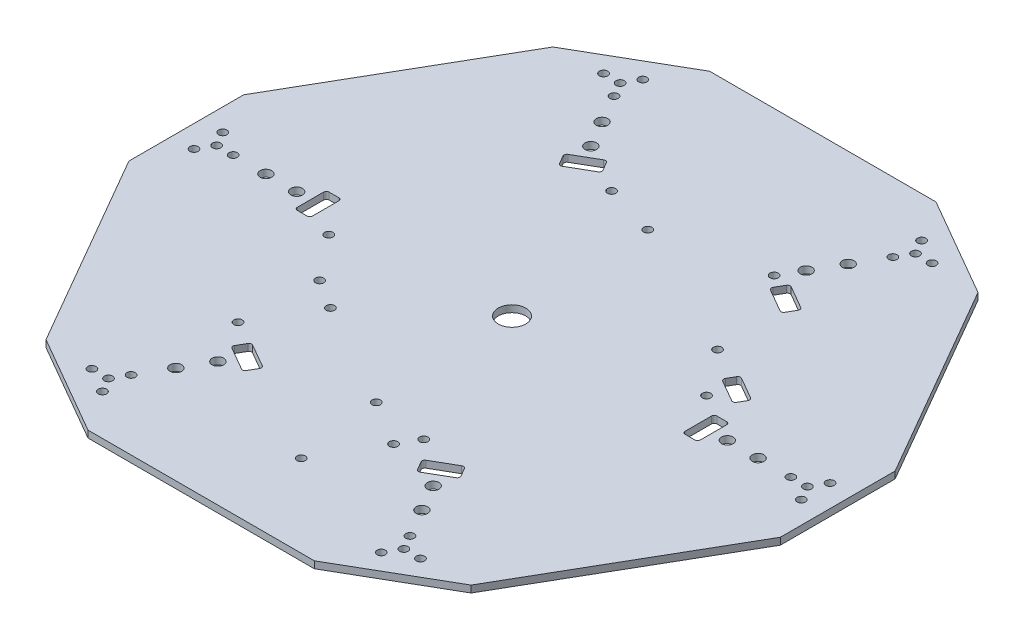
SolidWorks part; units mm, degrees
ref_plane "前视基准面" through (0, 0, 0) normal (0, 0, 1) x (1, 0, 0)
ref_plane "上视基准面" through (0, 0, 0) normal (0, 1, 0) x (1, 0, 0)
ref_plane "右视基准面" through (0, 0, 0) normal (1, 0, 0) x (0, 0, -1)
other "Configuration Table"
sketch "草图2" plane through (0, 0, 0) normal (0, 1, 0) x (1, 0, 0)
  line L1 (45, 0) -> (22.5, 38.9711)
  line L2 (22.5, 38.9711) -> (-22.5, 38.9711)
  line L3 (-22.5, 38.9711) -> (-45, 0)
  line L4 (-45, 0) -> (-22.5, -38.9711)
  line L5 (-22.5, -38.9711) -> (22.5, -38.9711)
  line L6 (22.5, -38.9711) -> (45, 0)
  line L7 (-54.5, 0) -> (-27.25, -47.1984)
  line L8 (-27.25, -47.1984) -> (27.25, -47.1984)
  line L9 (27.25, -47.1984) -> (54.5, 0)
  line L10 (54.5, 0) -> (27.25, 47.1984)
  line L11 (27.25, 47.1984) -> (-27.25, 47.1984)
  line L12 (-27.25, 47.1984) -> (-54.5, 0)
  circle A0 centre (0, 0) radius 38.9711 construction
  circle A1 centre (0, 0) radius 47.1984 construction
  circle A2 centre (0, 0) radius 5
  dimension "D3" = 10
  dimension "D1" = 45
  dimension "D2" = 9.5
extrude "凸台-拉伸1" add sketch "草图2" along normal blind 2.5 contours L5 L6 L1 L2 L3 L4 | L11 L12 L7 L8 L9 L10 L6 L5 L4 L3 L2 L1
sketch "草图3" plane through (0, 2.5, 0) normal (0, 1, 0) x (1, 0, 0)
  line L7 (-45, 0) -> (-22.5, -38.9711) construction
  line L8 (-22.5, -38.9711) -> (22.5, -38.9711) construction
  line L9 (22.5, -38.9711) -> (45, 0) construction
  line L10 (45, 0) -> (22.5, 38.9711) construction
  line L11 (22.5, 38.9711) -> (-22.5, 38.9711) construction
  line L12 (-22.5, 38.9711) -> (-45, 0) construction
  circle A0 centre (0, 0) radius 38.9711 construction
  circle A7 centre (-22.5, 38.9711) radius 2.1
  circle A8 centre (22.5, 38.9711) radius 2.1
  circle A9 centre (45, 0) radius 2.1
  circle A10 centre (22.5, -38.9711) radius 2.1
  circle A11 centre (-22.5, -38.9711) radius 2.1
  circle A12 centre (-45, 0) radius 2.1
  point P23 (0, 0)
  point P24 (0, 0)
  dimension "D2" = 4.2
  dimension "D1" = 45
  dimension "D3" = 6
extrude "切除-拉伸1" [suppressed] cut sketch "草图3" against normal blind 2.5
sketch "草图4" plane through (0, 2.5, 0) normal (0, 1, 0) x (1, 0, 0)
  line L0 (-27.25, 47.1984) -> (-54.5, 0) construction
  line L1 (-54.5, 0) -> (-27.25, -47.1984)
  line L2 (-27.25, -47.1984) -> (27.25, -47.1984)
  line L3 (27.25, -47.1984) -> (54.5, 0)
  line L4 (54.5, 0) -> (27.25, 47.1984)
  line L5 (27.25, 47.1984) -> (-27.25, 47.1984)
  line L6 (-27.25, 47.1984) -> (-54.5, 0)
  line L7 (-100.688, 0) -> (-50.344, -87.1984)
  line L8 (-50.344, -87.1984) -> (50.344, -87.1984)
  line L9 (50.344, -87.1984) -> (100.688, 0)
  line L10 (100.688, 0) -> (50.344, 87.1984)
  line L11 (50.344, 87.1984) -> (-50.344, 87.1984)
  line L12 (-50.344, 87.1984) -> (-100.688, 0)
  circle A0 centre (0, 0) radius 47.1984 construction
  circle A1 centre (0, 0) radius 87.1984 construction
  dimension "D1" = 40
extrude "凸台-拉伸2" add sketch "草图4" against normal up to surface (2.5 mm away) up to face at (0, 0, 5)
sketch "草图5" plane through (0, 2.5, 0) normal (0, 1, 0) x (1, 0, 0)
  line L0 (-50.344, 87.1984) -> (-100.688, 0) construction
  line L1 (-89.141, 0) -> (-44.5705, -77.1984) construction
  line L2 (-44.5705, -77.1984) -> (44.5705, -77.1984) construction
  line L3 (44.5705, -77.1984) -> (89.141, 0) construction
  line L4 (89.141, 0) -> (44.5705, 77.1984) construction
  line L5 (44.5705, 77.1984) -> (-44.5705, 77.1984) construction
  line L6 (-44.5705, 77.1984) -> (-89.141, 0) construction
  circle A0 centre (0, 0) radius 77.1984 construction
  circle A1 centre (-44.5705, 77.1984) radius 2.1
  circle A2 centre (44.5705, 77.1984) radius 2.1
  circle A3 centre (89.141, 0) radius 2.1
  circle A4 centre (44.5705, -77.1984) radius 2.1
  circle A5 centre (-44.5705, -77.1984) radius 2.1
  circle A6 centre (-89.141, 0) radius 2.1
  point P24 (0, 0)
  dimension "D2" = 4.2
  dimension "D1" = 10
  dimension "D3" = 6
extrude "切除-拉伸2" cut sketch "草图5" against normal blind 10
sketch "草图8" plane through (0, 2.5, 0) normal (0, 1, 0) x (1, 0, 0)
  line L0 (50.344, 87.1984) -> (-50.344, 87.1984) construction
  line L1 (-100.688, 0) -> (-50.344, -87.1984) construction
  circle A0 centre (-44.5705, 77.1984) radius 10
  circle A1 centre (44.5705, 77.1984) radius 10
  circle A2 centre (89.141, 0) radius 10
  circle A3 centre (44.5705, -77.1984) radius 10
  circle A4 centre (-44.5705, -77.1984) radius 10
  circle A5 centre (-89.141, 0) radius 10
  circle A6 centre (-113.6008, 65.5875) radius 60
  circle A7 centre (0, 131.175) radius 60
  circle A8 centre (113.6008, 65.5875) radius 60
  circle A9 centre (113.6008, -65.5875) radius 60
  circle A10 centre (0, -131.175) radius 60
  circle A11 centre (-113.6008, -65.5875) radius 60
  point P36 (0, 0)
  line M23 (-50.344, 87.1984) -> (-100.688, 0)
  line M24 (-100.688, 0) -> (-50.344, -87.1984)
  line M25 (-50.344, -87.1984) -> (50.344, -87.1984)
  line M26 (50.344, -87.1984) -> (100.688, 0)
  line M27 (100.688, 0) -> (50.344, 87.1984)
  line M28 (50.344, 87.1984) -> (-50.344, 87.1984)
  dimension "D1" = 120
  dimension "D2" = 6
extrude "切除-拉伸3" cut sketch "草图8" against normal blind 10 contours A0 M28 M23 | A7 A0 M28 | A6 A0 M23 | A7 M28 | A8 M27 | A9 M26 | A10 M25 | A11 M24 | A6 M23 | A1 M27 M28 | A7 A1 M28 | A8 A1 M27 | A8 A2 M27 | A2 M26 M27 | A9 A2 M26 | A9 A3 M26 | A10 A3 M25 | A3 M25 M26 | A11 A4 M24 | A4 M24 M25 | A10 A4 M25 | A5 M23 M24 | A6 A5 M23 | A11 A5 M24
sketch "草图10" plane through (0, 2.5, 0) normal (0, 1, 0) x (1, 0, 0)
  line L0 (-123, 12.1244) -> (-123, -12.1244)
  line L1 (-130, 0) -> (-65, -112.5833)
  line L2 (-65, -112.5833) -> (65, -112.5833)
  line L3 (65, -112.5833) -> (130, 0)
  line L4 (130, 0) -> (65, 112.5833)
  line L5 (65, 112.5833) -> (-65, 112.5833)
  line L6 (-65, 112.5833) -> (-130, 0)
  line L7 (-51, 112.5833) -> (-72, 100.4589)
  line L8 (72, 100.4589) -> (51, 112.5833)
  line L9 (123, -12.1244) -> (123, 12.1244)
  line L10 (51, -112.5833) -> (72, -100.4589)
  line L11 (-72, -100.4589) -> (-51, -112.5833)
  circle A0 centre (0, 0) radius 112.5833 construction
  arc A3 (-38.2033, 84.9093) -> (38.2033, 84.9093) centre (0, 131.175) ccw
  arc A5 (-38.2033, 84.9093) -> (38.2033, 84.9093) centre (0, 131.175) ccw
  arc A17 (-38.2033, 84.9093) -> (-54.432, 75.5397) centre (-44.5705, 77.1984) ccw
  arc A18 (-38.2033, 84.9093) -> (-54.432, 75.5397) centre (-44.5705, 77.1984) ccw
  arc A19 (-92.6353, 9.3696) -> (-54.432, 75.5397) centre (-113.6008, 65.5875) ccw
  arc A20 (-92.6353, 9.3696) -> (-54.432, 75.5397) centre (-113.6008, 65.5875) ccw
  arc A21 (-92.6353, 9.3696) -> (-92.6353, -9.3696) centre (-89.141, 0) ccw
  arc A22 (-92.6353, 9.3696) -> (-92.6353, -9.3696) centre (-89.141, 0) ccw
  arc A23 (-54.432, -75.5397) -> (-92.6353, -9.3696) centre (-113.6008, -65.5875) ccw
  arc A36 (-54.432, -75.5397) -> (-92.6353, -9.3696) centre (-113.6008, -65.5875) ccw
  arc A37 (-54.432, -75.5397) -> (-38.2033, -84.9093) centre (-44.5705, -77.1984) ccw
  arc A38 (-54.432, -75.5397) -> (-38.2033, -84.9093) centre (-44.5705, -77.1984) ccw
  arc A39 (38.2033, -84.9093) -> (-38.2033, -84.9093) centre (0, -131.175) ccw
  arc A40 (38.2033, -84.9093) -> (-38.2033, -84.9093) centre (0, -131.175) ccw
  arc A41 (38.2033, -84.9093) -> (54.432, -75.5397) centre (44.5705, -77.1984) ccw
  arc A42 (38.2033, -84.9093) -> (54.432, -75.5397) centre (44.5705, -77.1984) ccw
  arc A43 (92.6353, -9.3696) -> (54.432, -75.5397) centre (113.6008, -65.5875) ccw
  arc A44 (92.6353, -9.3696) -> (54.432, -75.5397) centre (113.6008, -65.5875) ccw
  arc A45 (92.6353, -9.3696) -> (92.6353, 9.3696) centre (89.141, 0) ccw
  arc A46 (92.6353, -9.3696) -> (92.6353, 9.3696) centre (89.141, 0) ccw
  arc A47 (54.432, 75.5397) -> (92.6353, 9.3696) centre (113.6008, 65.5875) ccw
  arc A48 (54.432, 75.5397) -> (92.6353, 9.3696) centre (113.6008, 65.5875) ccw
  arc A49 (54.432, 75.5397) -> (38.2033, 84.9093) centre (44.5705, 77.1984) ccw
  arc A50 (54.432, 75.5397) -> (38.2033, 84.9093) centre (44.5705, 77.1984) ccw
  point P47 (0, 0)
  arc M32 (38.2033, 84.9093) -> (-38.2033, 84.9093) centre (0, 131.175) cw
  arc M33 (-38.2033, 84.9093) -> (-54.432, 75.5397) centre (-44.5705, 77.1984) ccw
  arc M34 (-54.432, 75.5397) -> (-92.6353, 9.3696) centre (-113.6008, 65.5875) cw
  arc M35 (-92.6353, 9.3696) -> (-92.6353, -9.3696) centre (-89.141, 0) ccw
  arc M36 (-92.6353, -9.3696) -> (-54.432, -75.5397) centre (-113.6008, -65.5875) cw
  arc M37 (-54.432, -75.5397) -> (-38.2033, -84.9093) centre (-44.5705, -77.1984) ccw
  arc M38 (-38.2033, -84.9093) -> (38.2033, -84.9093) centre (0, -131.175) cw
  arc M39 (38.2033, -84.9093) -> (54.432, -75.5397) centre (44.5705, -77.1984) ccw
  arc M40 (54.432, -75.5397) -> (92.6353, -9.3696) centre (113.6008, -65.5875) cw
  arc M41 (92.6353, -9.3696) -> (92.6353, 9.3696) centre (89.141, 0) ccw
  arc M42 (92.6353, 9.3696) -> (54.432, 75.5397) centre (113.6008, 65.5875) cw
  arc M43 (54.432, 75.5397) -> (38.2033, 84.9093) centre (44.5705, 77.1984) ccw
  dimension "D2" = 130
  dimension "D3" = 7
  dimension "D1" = 0
  dimension "D4" = 6
extrude "凸台-拉伸3" add sketch "草图10" against normal up to surface (2.5 mm away) contours L1 L11 L2 L10 L3 L9 L4 L8 L5 L7 L6 L0 M32 M43 M42 M41 M40 M39 M38 M37 M36 M35 M34 M33 up to face at (-89.141, 0, 2.1)
sketch "草图11" plane through (0, 2.5, 0) normal (0, 1, 0) x (1, 0, 0)
  line L0 (-123, 12.1244) -> (-123, -12.1244) construction
  line L1 (-123, 0) -> (-107, 0) construction
  line L2 (-107, 0) -> (-101, 0) construction
  circle A0 centre (-107, 0) radius 1.5
  circle A1 centre (-101, 0) radius 1.5
  circle A2 centre (-110, -5.1962) radius 1.5
  circle A3 centre (-110, 5.1962) radius 1.5
  point P12 (-107, 0)
  dimension "D1" = 3
  dimension "D2" = 16
  dimension "D3" = 6
  dimension "D4" = 3
extrude "切除-拉伸4" cut sketch "草图11" against normal through all
pattern_circular "阵列(圆周)1" count 6 over 360 about axis through (0, 0, 0) along (0, 1, 0) of "切除-拉伸4"
sketch "草图12" plane through (0, 2.5, 0) normal (0, 1, 0) x (1, 0, 0)
  line L0 (0, 0) -> (60.8571, 0) construction
  line L1 (-118, 68.1273) -> (-118, -68.1273)
  line L2 (-118, -68.1273) -> (0, -136.2547)
  line L3 (0, -136.2547) -> (118, -68.1273)
  line L4 (118, -68.1273) -> (118, 68.1273)
  line L5 (118, 68.1273) -> (0, 136.2547)
  line L6 (0, 136.2547) -> (-118, 68.1273)
  line L7 (-51, 112.5833) -> (-72, 100.4589) construction
  line L9 (-145.896, 84.2331) -> (-145.896, -84.2331)
  line L10 (-145.896, -84.2331) -> (0, -168.4662)
  line L11 (0, -168.4662) -> (145.896, -84.2331)
  line L12 (145.896, -84.2331) -> (145.896, 84.2331)
  line L13 (145.896, 84.2331) -> (0, 168.4662)
  line L14 (0, 168.4662) -> (-145.896, 84.2331)
  circle A0 centre (0, 0) radius 118 construction
  circle A1 centre (0, 0) radius 145.896 construction
  line M51 (-123, -12.1244) -> (-72, -100.4589)
  line M52 (-72, -100.4589) -> (-51, -112.5833)
  line M53 (-51, -112.5833) -> (51, -112.5833)
  line M54 (51, -112.5833) -> (72, -100.4589)
  line M55 (72, -100.4589) -> (123, -12.1244)
  line M56 (123, -12.1244) -> (123, 12.1244)
  line M57 (123, 12.1244) -> (72, 100.4589)
  line M58 (72, 100.4589) -> (51, 112.5833)
  line M59 (51, 112.5833) -> (-51, 112.5833)
  line M60 (-51, 112.5833) -> (-72, 100.4589)
  line M61 (-72, 100.4589) -> (-123, 12.1244)
  line M62 (-123, 12.1244) -> (-123, -12.1244)
  dimension "D1" = 5
extrude "切除-拉伸12" cut sketch "草图12" against normal up to surface (2.5 mm away) contours L13 L14 L9 L10 L11 L12 L6 L5 L4 L3 L2 L1 M59 M58 M57 M56 M55 M54 M53 M52 M51 M62 M61 M60 | L3 M53 M54 M55 | L2 M51 M52 M53 | L1 M61 M62 M51 | L6 M59 M60 M61 | L5 M57 M58 M59 | L4 M55 M56 M57
sketch "草图13" plane through (0, 2.5, 0) normal (0, 1, 0) x (1, 0, 0)
  circle A0 centre (-78, 0) radius 2.1
  circle A2 centre (-39, 67.55) radius 2.1
  circle A3 centre (39, 67.55) radius 2.1
  circle A4 centre (78, 0) radius 2.1
  circle A5 centre (39, -67.55) radius 2.1
  circle A6 centre (-39, -67.55) radius 2.1
  point P16 (0, 0)
  dimension "D1" = 4.2
  dimension "D2" = 78
  dimension "D3" = 6
extrude "切除-拉伸13" cut sketch "草图13" against normal blind 10
sketch "草图14" plane through (0, 2.5, 0) normal (0, 1, 0) x (1, 0, 0)
  line L0 (-2.4987, 51.6721) -> (45.9987, 23.6721) construction
  line L1 (45.9987, 23.6721) -> (2.4987, -51.6721) construction
  line L2 (2.4987, -51.6721) -> (-45.9987, -23.6721) construction
  line L3 (-45.9987, -23.6721) -> (-2.4987, 51.6721) construction
  line L4 (0, 0) -> (155.2897, 0) construction
  line L5 (-24.2487, 14) -> (24.2487, -14) construction
  line L6 (45.9987, 23.6721) -> (57.162, 43.0074) construction
  circle A0 centre (-2.4987, 51.6721) radius 1.5
  circle A1 centre (-45.9987, -23.6721) radius 1.5
  circle A2 centre (2.4987, -51.6721) radius 1.5
  circle A3 centre (47.7487, 26.7032) radius 1.5
  dimension "D5" = 3
  dimension "D1" = 30
  dimension "D2" = 28
  dimension "D3" = 87
  dimension "D4" = 28
  dimension "D6" = 3.5
extrude "切除-拉伸14" cut sketch "草图14" against normal blind 10
sketch "草图15" plane through (0, 2.5, 0) normal (0, 1, 0) x (1, 0, 0)
  line L0 (-58.7032, -7.6769) -> (22.7032, -54.6769) construction
  line L1 (22.7032, -54.6769) -> (60.2032, 10.275) construction
  line L2 (60.2032, 10.275) -> (-21.2032, 57.275) construction
  line L3 (-21.2032, 57.275) -> (-58.7032, -7.6769) construction
  line L4 (19.5, 33.775) -> (-18, -31.1769) construction
  line L5 (0, 0) -> (68.6706, 0) construction
  circle A0 centre (-21.2032, 57.275) radius 1.5
  circle A1 centre (60.2032, 10.275) radius 1.5
  circle A2 centre (22.7032, -54.6769) radius 1.5
  circle A3 centre (-58.7032, -7.6769) radius 1.5
  dimension "D3" = 3
  dimension "D1" = 94
  dimension "D2" = 75
  dimension "D4" = 39
  dimension "D5" = 30
extrude "切除-拉伸15" cut sketch "草图15" against normal blind 10
sketch "草图16" plane through (0, 0, 0) normal (0, -1, 0) x (-1, 0, 0)
  line L0 (-57.7175, 18.2197) -> (-67.2438, 12.7197)
  line L1 (-67.2438, 12.7197) -> (-69.7438, 17.0498)
  line L2 (-69.7438, 17.0498) -> (-60.2175, 22.5498)
  line L3 (-60.2175, 22.5498) -> (-57.7175, 18.2197)
  line L4 (45.9987, -23.6721) -> (-2.4987, -51.6721) construction
  line L5 (-39, 67.55) -> (0, 0) construction
  line L6 (-31.75, 54.9926) -> (-52.8668, 42.8008) construction
  line L7 (-22.7032, -54.6769) -> (-6.4532, -82.8227) construction
  line L8 (-6.4532, -82.8227) -> (47.6734, -51.5727) construction
  line L9 (47.6734, -51.5727) -> (31.4234, -23.4269) construction
  line L10 (31.4234, -23.4269) -> (-22.7032, -54.6769) construction
  line L11 (-18.7032, -61.6051) -> (35.4234, -30.3551) construction
  circle A0 centre (-34.75, 60.1888) radius 1.5
  circle A1 centre (-18.7032, -61.6051) radius 1.5
  circle A2 centre (-6.4532, -82.8227) radius 1.5
  circle A3 centre (47.6734, -51.5727) radius 1.5
  circle A4 centre (35.4234, -30.3551) radius 1.5
  dimension "D4" = 3
  dimension "D9" = 3
  dimension "D1" = 11
  dimension "D2" = 5
  dimension "D3" = 14.5
  dimension "D5" = 6
  dimension "D6" = 8
  dimension "D7" = 24.5
  dimension "D8" = 62.5
extrude "切除-拉伸16" cut sketch "草图16" against normal blind 10
sketch "草图17" plane through (0, 0, 0) normal (0, -1, 0) x (1, 0, 0)
  line L0 (-41.4796, 60.3449) -> (-31.5204, 66.0949)
  line L1 (-31.5204, 66.0949) -> (-28.7704, 61.3317)
  line L2 (-28.7704, 61.3317) -> (-38.7296, 55.5817)
  line L3 (-38.7296, 55.5817) -> (-41.4796, 60.3449)
  line L5 (-44.5705, 77.1984) -> (-39, 67.55) construction
  dimension "D1" = 11.5
  dimension "D2" = 5.5
  dimension "D3" = 5
extrude "切除-拉伸17" cut sketch "草图17" against normal blind 10
fillet "圆角1" radius 1 4 edges at (-38.7296, 1.25, 55.5817) (-41.4796, 1.25, 60.3449) (-28.7704, 1.25, 61.3317) (-31.5204, 1.25, 66.0949)
pattern_circular "阵列(圆周)2" count 6 over 360 about axis through (0, 0, 0) along (0, 1, 0) skipping 3 of "圆角1", "切除-拉伸17"
sketch "草图18" plane through (0, 0, 0) normal (0, -1, 0) x (1, 0, 0)
  line L0 (37.7925, -55.4585) -> (40.5425, -60.2216)
  line L1 (40.5425, -60.2216) -> (50.5018, -54.4716)
  line L2 (50.5018, -54.4716) -> (47.7518, -49.7085)
  line L3 (47.7518, -49.7085) -> (37.7925, -55.4585)
  line L4 (34.75, -60.1888) -> (39, -67.55) construction
  dimension "D1" = 11.5
  dimension "D2" = 5.5
  dimension "D3" = 5
extrude "切除-拉伸18" cut sketch "草图18" against normal blind 10
fillet "圆角2" radius 1 4 edges at (40.5425, 1.25, -60.2216) (50.5018, 1.25, -54.4716) (47.7518, 1.25, -49.7085) (37.7925, 1.25, -55.4585)
fillet "圆角3" radius 1 4 edges at (67.2438, 1.25, -12.7197) (69.7438, 1.25, -17.0498) (57.7175, 1.25, -18.2197) (60.2175, 1.25, -22.5498)
